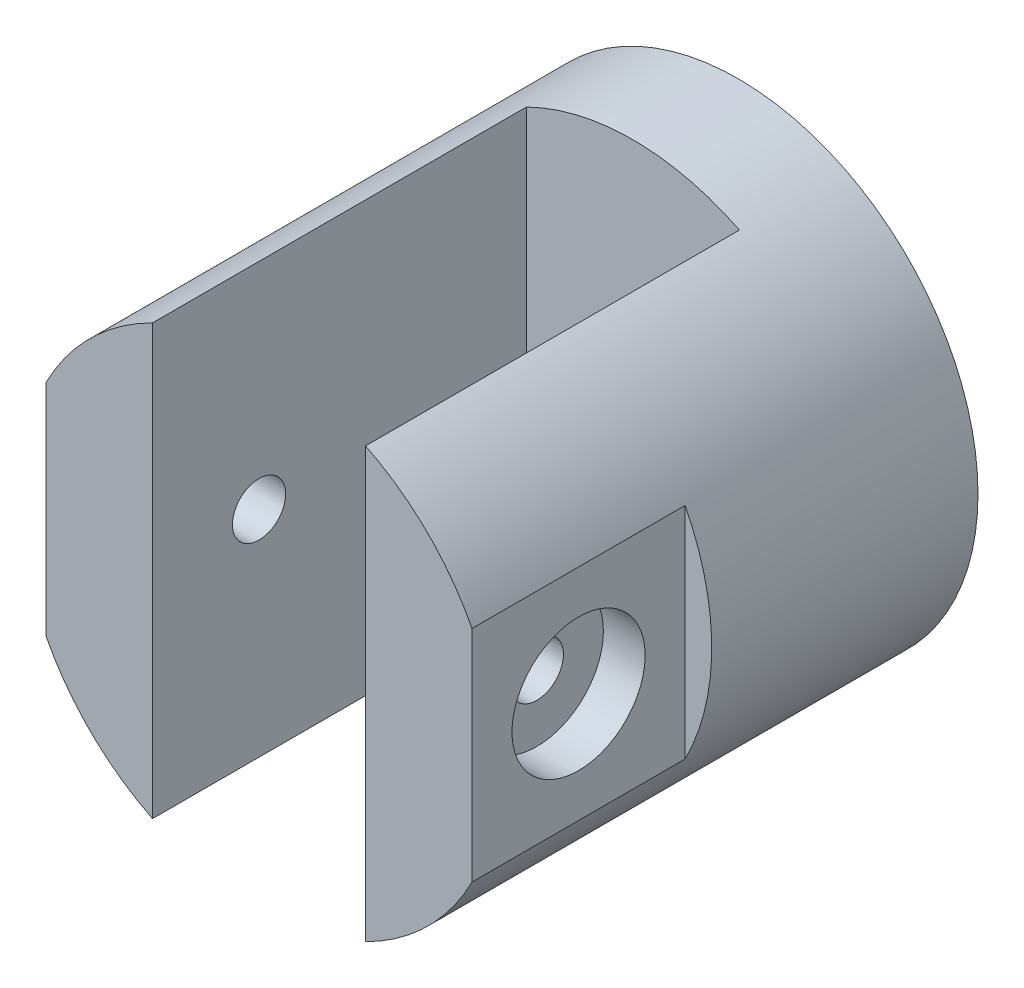
SolidWorks part; units mm, degrees
material "6061 Alloy"
ref_plane "Front Plane" through (0, 0, 0) normal (0, 0, 1) x (1, 0, 0)
ref_plane "Top Plane" through (0, 0, 0) normal (0, 1, 0) x (1, 0, 0)
ref_plane "Right Plane" through (0, 0, 0) normal (1, 0, 0) x (0, 0, -1)
sketch "Sketch1" plane through (0, 0, 0) normal (0, 0, 1) x (1, 0, 0)
  circle A0 centre (0, 0) radius 28.575
  dimension "D1" = 57.15
extrude "OD Don't Care" add sketch "Sketch1" along normal blind 57.15
sketch "Sketch3" plane through (0, 0, 0) normal (0, 1, 0) x (1, 0, 0)
  line L0 (-28.575, -57.15) -> (28.575, -57.15) construction
  line L1 (-12.7, -12.573) -> (12.7, -12.573)
  line L2 (-12.7, -12.573) -> (-12.7, -57.15)
  line L3 (-12.7, -57.15) -> (12.7, -57.15)
  line L4 (12.7, -12.573) -> (12.7, -57.15)
  line L5 (-12.7, -12.573) -> (12.7, -57.15) construction
  line L6 (-12.7, -57.15) -> (12.7, -12.573) construction
  line L7 (28.575, 0) -> (-28.575, 0) construction
  point P0 (0, -34.8615)
  dimension "D1" = 25.4
  dimension "D2" = 12.573
extrude "Slot" cut sketch "Sketch3" against normal mid plane 101.6
sketch "Sketch4" plane through (0, 0, 12.573) normal (0, 0, 1) x (1, 0, 0)
  circle A0 centre (0, 0) radius 7.9375
  dimension "D1" = 15.875
extrude "5/8\" Through Hole" cut sketch "Sketch4" against normal through all
sketch "Sketch5" plane through (0, 0, 57.15) normal (0, 0, 1) x (1, 0, 0)
  line L0 (-12.7, 0) -> (25.4, 0) construction
  line L1 (25.4, -25.5977) -> (-28.575, -25.5977)
  line L2 (25.4, -25.5977) -> (25.4, 25.5977)
  line L3 (25.4, 25.5977) -> (-28.575, 25.5977)
  line L4 (-28.575, -25.5977) -> (-28.575, 25.5977)
  line L5 (25.4, -25.5977) -> (-28.575, 25.5977) construction
  line L6 (25.4, 25.5977) -> (-28.575, -25.5977) construction
  line L7 (-12.7, -25.5977) -> (-12.7, 25.5977) construction
  arc A0 (-12.7, 25.5977) -> (-12.7, -25.5977) centre (0, 0) ccw construction
  point P0 (-1.5875, 0)
  dimension "D1" = 38.1
extrude "Flat Surface" cut sketch "Sketch5" against normal blind 25.4 flip side to cut
sketch "Sketch2" plane through (25.4, 0, 0) normal (1, 0, 0) x (0, 0, -1)
  line L0 (-57.15, 28.575) -> (-57.15, -28.575) construction
  circle A0 centre (-44.45, 0) radius 3.175
  dimension "D1" = 6.35
  dimension "D2" = 12.7
extrude "1/4\" Through Hole" cut sketch "Sketch2" against normal through all
sketch "Sketch6" plane through (25.4, 0, 0) normal (1, 0, 0) x (0, 0, -1)
  circle A0 centre (-44.45, 0) radius 7.9375
  dimension "D1" = 15.875
extrude "Cut-Extrude1" cut sketch "Sketch6" against normal blind 4.9784
sketch "Sketch7" plane through (0, 0, 57.15) normal (0, 0, 1) x (1, 0, 0)
  line L0 (-12.7, -13.0909) -> (-25.4, -13.0909) construction
  line L2 (-25.4, -13.0909) -> (-25.4, 13.0909)
  line L3 (-12.7, 13.0909) -> (-25.4, 13.0909) construction
  line L4 (-12.7, -25.5977) -> (-12.7, 25.5977) construction
  arc A0 (-12.7, 25.5977) -> (-12.7, -25.5977) centre (0, 0) ccw construction
  point P9 (-25.4, 13.0909)
  point P10 (-25.4, -13.0909)
  dimension "D1" = 12.7
  dimension "D2" = 26.1817
extrude "Cut-Extrude2" cut sketch "Sketch7" against normal blind 25.4 and the other way through all
sketch "Sketch8" plane through (-25.4, 0, 0) normal (-1, 0, 0) x (0, 0, 1)
  circle A0 centre (44.45, 0) radius 7.9375
  dimension "D1" = 15.875
extrude "Cut-Extrude3" cut sketch "Sketch8" against normal blind 4.9784
